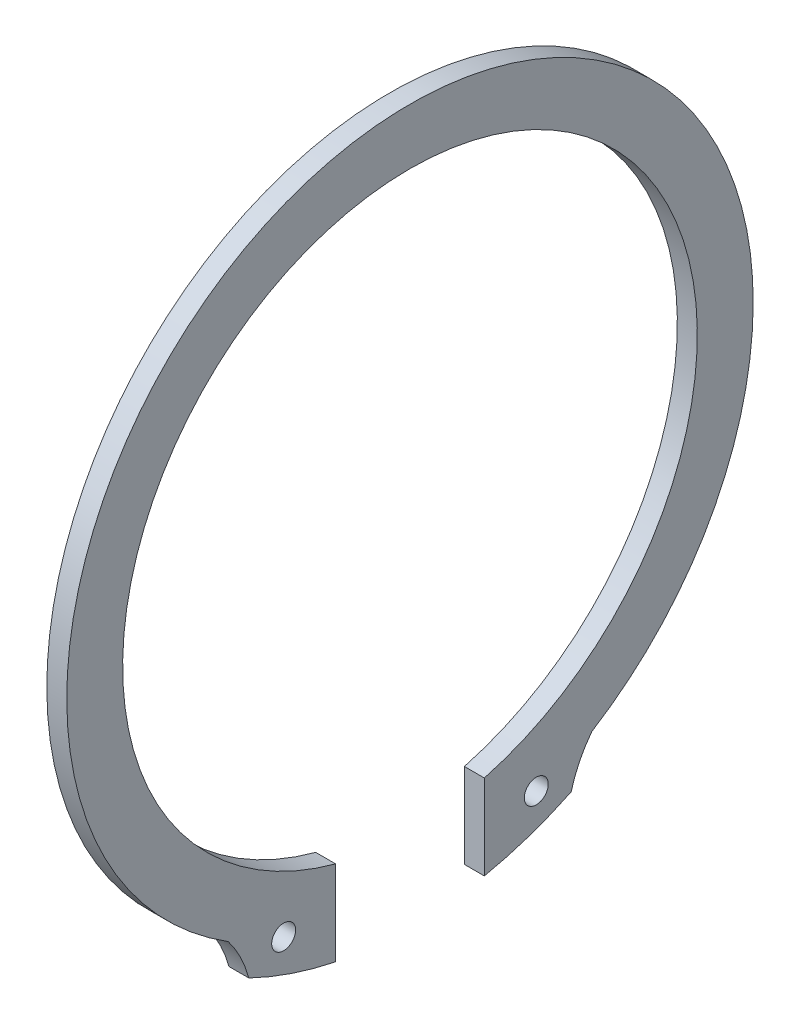
SolidWorks part; units mm, degrees
ref_plane "Front" through (0, 0, 0) normal (0, 0, 1) x (1, 0, 0)
ref_plane "Top" through (0, 0, 0) normal (0, 1, 0) x (1, 0, 0)
ref_plane "Right" through (0, 0, 0) normal (1, 0, 0) x (0, 0, -1)
sketch "Esquisse1" plane through (0, 0, 0) normal (1, 0, 0) x (0, 0, -1)
  line L0 (0, 0) -> (-9.3175, -34.7733) construction
  line L1 (0, 0) -> (0, -81.578) construction
  line L2 (-9.3175, -34.7733) -> (-9.3175, -45.4038)
  line L3 (9.3175, -34.7733) -> (9.3175, -45.4038)
  arc A0 (-20.1944, -41.7194) -> (-9.3175, -45.4038) centre (0, 0) ccw
  arc A1 (9.3175, -34.7733) -> (-9.3175, -34.7733) centre (0, 0) ccw
  arc A2 (22.7822, -36.4688) -> (-22.7822, -36.4688) centre (0, 0) ccw
  arc A4 (20.1944, -41.7194) -> (9.3175, -45.4038) centre (0, 0) cw
  circle A5 centre (0, 0) radius 43 construction
  arc A6 (-20.1944, -41.7194) -> (-22.7822, -36.4688) centre (-34.6843, -45.5978) ccw
  arc A7 (20.1944, -41.7194) -> (22.7822, -36.4688) centre (34.6843, -45.5978) cw
  circle A8 centre (0, 0) radius 36 construction
  circle A9 centre (-15.8261, -39.4411) radius 1.5
  circle A10 centre (15.8261, -39.4411) radius 1.5
  point P11 (20.1944, -41.7194)
  point P12 (-20.1944, -41.7194)
  point P19 (-21.5105, -36.3643)
  point P20 (-22.7822, -36.3643)
  point P22 (21.5105, -36.3643)
  dimension "D1" = 92.7
  dimension "D2" = 72
  dimension "D4" = 3
  dimension "D5" = 15
  dimension "D6" = 15
  dimension "D3" = 7
extrude "Boss.-Extru.1" add sketch "Esquisse1" along normal blind 2.5
